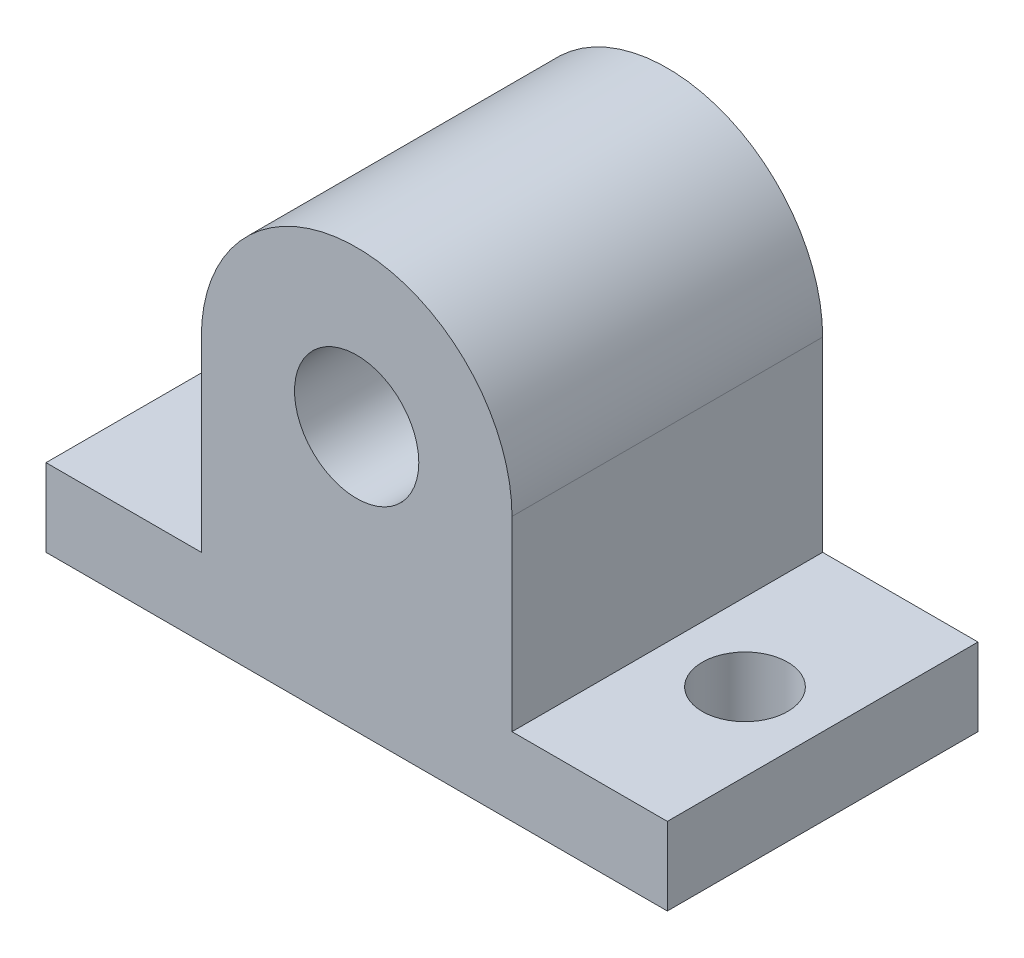
SolidWorks part; units mm, degrees
ref_plane "前视基准面" through (0, 0, 0) normal (0, 0, 1) x (1, 0, 0)
ref_plane "上视基准面" through (0, 0, 0) normal (0, 1, 0) x (1, 0, 0)
ref_plane "右视基准面" through (0, 0, 0) normal (1, 0, 0) x (0, 0, -1)
sketch "草图1" plane through (0, 0, 0) normal (0, 1, 0) x (1, 0, 0)
  line L1 (-16.478, 4.8428) -> (23.522, 4.8428)
  line L2 (-16.478, 4.8428) -> (-16.478, -15.1572)
  line L3 (-16.478, -15.1572) -> (23.522, -15.1572)
  line L4 (23.522, 4.8428) -> (23.522, -15.1572)
  line L5 (-16.478, 4.8428) -> (23.522, -15.1572) construction
  line L6 (-16.478, -15.1572) -> (23.522, 4.8428) construction
  point P4 (3.522, -5.1572)
  dimension "D1" = 40
  dimension "D2" = 20
extrude "凸台-拉伸1" add sketch "草图1" along normal blind 5
sketch "草图2" plane through (0, 0, 15.1572) normal (0, 0, 1) x (1, 0, 0)
  line L0 (3.522, 5) -> (3.522, 8.7926) construction
  line L2 (-16.478, 5) -> (23.522, 5) construction
  line L3 (-6.478, 17) -> (-6.478, 5)
  line L4 (13.522, 17) -> (13.522, 5)
  line L5 (13.522, 5) -> (-6.478, 5)
  circle A0 centre (3.522, 17) radius 4
  arc A1 (13.522, 17) -> (-6.478, 17) centre (3.522, 17) ccw
  dimension "D1" = 8
  dimension "D4" = 6
  dimension "D2" = 3.7926
  dimension "D3" = 12
extrude "凸台-拉伸2" add sketch "草图2" against normal up to surface (20 mm away) up to face at (3.522, 2.5, -4.8428)
sketch "草图3" plane through (0, 5, 0) normal (0, 1, 0) x (1, 0, 0)
  line L0 (-16.478, -5.1572) -> (23.522, -5.1572) construction
  line L1 (-16.478, 4.8428) -> (-16.478, -15.1572) construction
  line L2 (23.522, -15.1572) -> (23.522, 4.8428) construction
  line L3 (-11.478, 4.8428) -> (-11.478, -15.1572) construction
  line L4 (-6.478, 4.8428) -> (-16.478, 4.8428) construction
  line L5 (-16.478, -15.1572) -> (-6.478, -15.1572) construction
  line L6 (18.522, 4.8428) -> (18.522, -15.1572) construction
  line L7 (23.522, 4.8428) -> (13.522, 4.8428) construction
  line L8 (13.522, -15.1572) -> (23.522, -15.1572) construction
  circle A0 centre (-11.478, -5.1572) radius 2.75
  circle A1 centre (18.522, -5.1572) radius 2.75
  dimension "D1" = 5.5
extrude "切除-拉伸1" cut sketch "草图3" against normal through all
